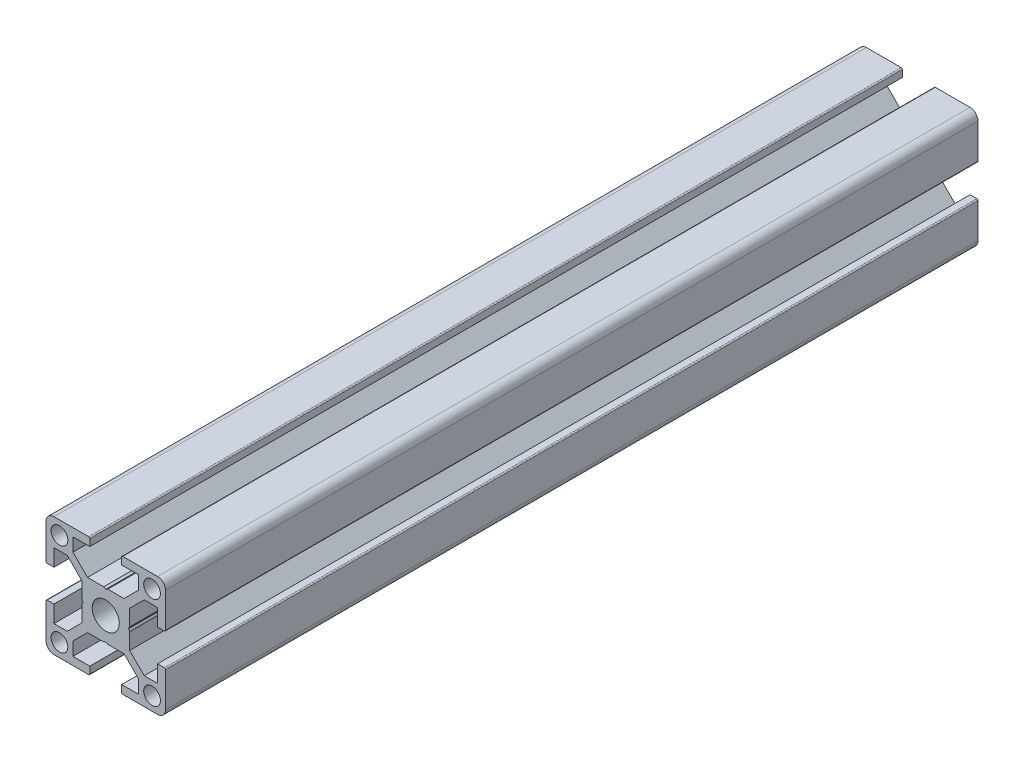
SolidWorks part; units mm, degrees
ref_plane "Front Plane" through (0, 0, 0) normal (0, 0, 1) x (1, 0, 0)
ref_plane "Top Plane" through (0, 0, 0) normal (0, 1, 0) x (1, 0, 0)
ref_plane "Right Plane" through (0, 0, 0) normal (1, 0, 0) x (0, 0, -1)
sketch "Sketch1" plane through (0, 0, 0) normal (0, 0, 1) x (1, 0, 0)
  line L0 (-14.7, 4) -> (-13, 4)
  line L1 (-13, 4) -> (-13, 8.25)
  line L2 (-13, 8.25) -> (-9.6642, 8.25)
  line L3 (-9.6642, 8.25) -> (-6, 4.5858)
  line L4 (-6, 4.5858) -> (-6, 0.5196)
  line L5 (-6, 0.5196) -> (-5.7, 0)
  line L6 (-5.7, 0) -> (-6, -0.5196)
  line L7 (-6, -0.5196) -> (-6, -4.5858)
  line L8 (-6, -4.5858) -> (-9.6642, -8.25)
  line L9 (-9.6642, -8.25) -> (-13, -8.25)
  line L10 (-13, -8.25) -> (-13, -4)
  line L11 (-13, -4) -> (-14.7, -4)
  line L12 (-15, -4.3) -> (-15, -13)
  line L13 (-13, -15) -> (-4.3, -15)
  line L14 (-4, -14.7) -> (-4, -13)
  line L15 (-4, -13) -> (-8.25, -13)
  line L16 (-8.25, -13) -> (-8.25, -9.6642)
  line L17 (-8.25, -9.6642) -> (-4.5858, -6)
  line L18 (-4.5858, -6) -> (-0.5196, -6)
  line L19 (-0.5196, -6) -> (0, -5.7)
  line L20 (0, -5.7) -> (0.5196, -6)
  line L21 (0.5196, -6) -> (4.5858, -6)
  line L22 (4.5858, -6) -> (8.25, -9.6642)
  line L23 (8.25, -9.6642) -> (8.25, -13)
  line L24 (8.25, -13) -> (4, -13)
  line L25 (4, -13) -> (4, -14.7)
  line L26 (4.3, -15) -> (13, -15)
  line L27 (15, -13) -> (15, -4.3)
  line L28 (14.7, -4) -> (13, -4)
  line L29 (13, -4) -> (13, -8.25)
  line L30 (13, -8.25) -> (9.6642, -8.25)
  line L31 (9.6642, -8.25) -> (6, -4.5858)
  line L32 (6, -4.5858) -> (6, -0.5196)
  line L33 (6, -0.5196) -> (5.7, 0)
  line L34 (5.7, 0) -> (6, 0.5196)
  line L35 (6, 0.5196) -> (6, 4.5858)
  line L36 (6, 4.5858) -> (9.6642, 8.25)
  line L37 (9.6642, 8.25) -> (13, 8.25)
  line L38 (13, 8.25) -> (13, 4)
  line L39 (13, 4) -> (14.7, 4)
  line L40 (15, 4.3) -> (15, 13)
  line L41 (13, 15) -> (4.3, 15)
  line L42 (4, 14.7) -> (4, 13)
  line L43 (4, 13) -> (8.25, 13)
  line L44 (8.25, 13) -> (8.25, 9.6642)
  line L45 (8.25, 9.6642) -> (4.5858, 6)
  line L46 (4.5858, 6) -> (0.5196, 6)
  line L47 (0.5196, 6) -> (0, 5.7)
  line L48 (0, 5.7) -> (-0.5196, 6)
  line L49 (-0.5196, 6) -> (-4.5858, 6)
  line L50 (-4.5858, 6) -> (-8.25, 9.6642)
  line L51 (-8.25, 9.6642) -> (-8.25, 13)
  line L52 (-8.25, 13) -> (-4, 13)
  line L53 (-4, 13) -> (-4, 14.7)
  line L54 (-4.3, 15) -> (-13, 15)
  line L55 (-15, 13) -> (-15, 4.3)
  arc A0 (-15, 4.3) -> (-14.7, 4) centre (-14.7, 4.3) ccw
  arc A1 (-14.7, -4) -> (-15, -4.3) centre (-14.7, -4.3) ccw
  arc A2 (-15, -13) -> (-13, -15) centre (-13, -13) ccw
  arc A3 (-4.3, -15) -> (-4, -14.7) centre (-4.3, -14.7) ccw
  arc A4 (4, -14.7) -> (4.3, -15) centre (4.3, -14.7) ccw
  arc A5 (13, -15) -> (15, -13) centre (13, -13) ccw
  arc A6 (15, -4.3) -> (14.7, -4) centre (14.7, -4.3) ccw
  arc A7 (14.7, 4) -> (15, 4.3) centre (14.7, 4.3) ccw
  arc A8 (15, 13) -> (13, 15) centre (13, 13) ccw
  arc A9 (4.3, 15) -> (4, 14.7) centre (4.3, 14.7) ccw
  arc A10 (-4, 14.7) -> (-4.3, 15) centre (-4.3, 14.7) ccw
  arc A11 (-13, 15) -> (-15, 13) centre (-13, 13) ccw
  circle A12 centre (11.625, 11.625) radius 2.1
  circle A13 centre (11.625, -11.625) radius 2.1
  circle A14 centre (0, 0) radius 3.4
  circle A15 centre (-11.625, -11.625) radius 2.1
  circle A16 centre (-11.625, 11.625) radius 2.1
extrude "Boss-Extrude1" add sketch "Sketch1" along normal blind 204
